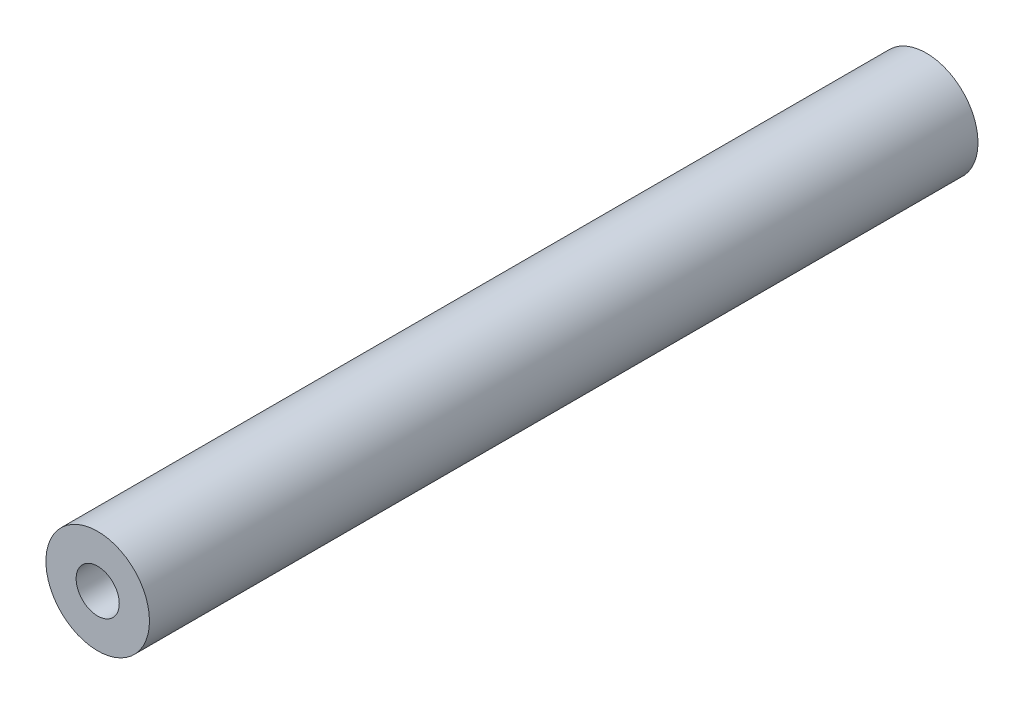
SolidWorks part; units mm, degrees
material "6061-T6 (SS)"
ref_plane "Front Plane" through (0, 0, 0) normal (0, 0, 1) x (1, 0, 0)
ref_plane "Top Plane" through (0, 0, 0) normal (0, 1, 0) x (1, 0, 0)
ref_plane "Right Plane" through (0, 0, 0) normal (1, 0, 0) x (0, 0, -1)
sketch "Sketch1" plane through (0, 0, 0) normal (0, 0, 1) x (1, 0, 0)
  circle A0 centre (0, 0) radius 3
  dimension "D1" = 6
extrude "Boss-Extrude1" add sketch "Sketch1" along normal mid plane 48 contours A0
hole_wizard "M3x0.5 Tapped Hole1" positions "3DSketch1" profile "Sketch2" tap size "M3x0.5" standard "ANSI Metric"
sketch3d "3DSketch1"
  line L0 (0, 0, 24) -> (0, 0, -24) construction
  point P0 (0, 0, 24)
sketch "Sketch2" plane through (0, 0, 24) normal (1, 0, 0) x (0, -1, 0)
  line L0 (0, 0) -> (0, 24.7511)
  line L1 (0, 24.7511) -> (1.25, 24)
  line L2 (1.25, 24) -> (1.25, 0)
  line L5 (1.25, 0) -> (0, 0)
  line L10 (0, 24.7511) -> (-1.25, 24) construction
  line L11 (0, -6.35) -> (0, 107.95) construction
  dimension "Tap Drill Dia." = 2.5
  dimension "Tap Drill Depth" = 24
  dimension "Drill Angle" = 118
cosmetic thread "Hole Thread1"
mirror "Mirror1" about plane through (0, 0, 0) normal (0, 0, 1) of "M3x0.5 Tapped Hole1"
cosmetic thread "Hole Thread2"
